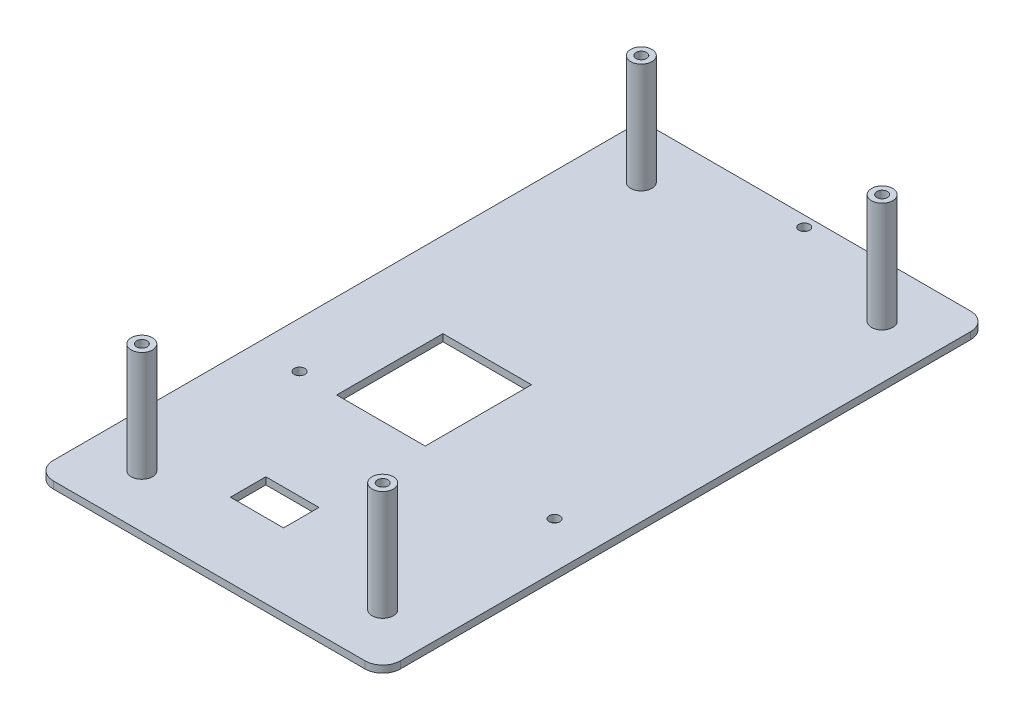
SolidWorks part; units mm, degrees
ref_plane "Alzado" through (0, 0, 0) normal (0, 0, 1) x (1, 0, 0)
ref_plane "Planta" through (0, 0, 0) normal (0, 1, 0) x (1, 0, 0)
ref_plane "Vista lateral" through (0, 0, 0) normal (1, 0, 0) x (0, 0, -1)
sketch "Croquis1" plane through (0, 0, 0) normal (0, 1, 0) x (1, 0, 0)
  line L0 (0, 5.5) -> (-25, 5.5)
  line L1 (-49, 85.5) -> (49, 85.5)
  line L2 (-49, 85.5) -> (-49, -85.5)
  line L3 (-49, -85.5) -> (49, -85.5)
  line L4 (49, 85.5) -> (49, -85.5)
  line L5 (-49, 85.5) -> (-42.196, 73.6277) construction
  line L6 (-49, -85.5) -> (49, 85.5) construction
  line L7 (0, -24.5) -> (-25, -24.5)
  line L8 (-25, 5.5) -> (-25, -24.5)
  line L9 (0, 0) -> (0, 5.5)
  line L10 (0, 5.5) -> (0, -24.5)
  line L11 (0, 0) -> (0, -8.409) construction
  line L12 (0, -64.5) -> (-15, -64.5)
  line L13 (0, -64.5) -> (0, -54.5)
  line L14 (0, -54.5) -> (-15, -54.5)
  line L15 (-15, -64.5) -> (-15, -54.5)
  point P0 (0, 0)
  dimension "D1" = 98
  dimension "D2" = 171
  dimension "D3" = 25
  dimension "D4" = 30
  dimension "D5" = 30
  dimension "D6" = 15
  dimension "D7" = 10
  dimension "D8" = 80
extrude "Saliente-Extruir1" add sketch "Croquis1" along normal blind 2 contours L4 L1 L2 L3 L9 L10 L7 L8 L0 L12 L15 L14 L13
fillet "Redondeo1" radius 5 4 edges at (49, 1, 85.5) (49, 1, -85.5) (-49, 1, -85.5) (-49, 1, 85.5)
sketch "Croquis2" plane through (0, 2, 0) normal (0, 1, 0) x (1, 0, 0)
  line L0 (0, -85.5) -> (0, 85.5) construction
  line L1 (-44, -85.5) -> (44, -85.5) construction
  line L2 (-44, 85.5) -> (44, 85.5) construction
  line L3 (-49, 80.5) -> (-49, -80.5) construction
  line L4 (49, 80.5) -> (49, -80.5) construction
  circle A0 centre (-36, -24) radius 1.5
  circle A1 centre (36, -24) radius 1.5
  circle A2 centre (0, 82.5) radius 1.5
  dimension "D1" = 3
  dimension "D2" = 3
  dimension "D3" = 61.5
  dimension "D5" = 13
  dimension "D7" = 3
  dimension "D4" = 61.5
  dimension "D6" = 13
  dimension "D8" = 106.5
extrude "Cortar-Extruir2" cut sketch "Croquis2" against normal blind 10 contours A1 | A0 | A2
sketch "Croquis5" plane through (0, 2, 0) normal (0, 1, 0) x (1, 0, 0)
  line L0 (-49, 80.5) -> (-49, -80.5) construction
  line L1 (-44, 85.5) -> (44, 85.5) construction
  line L2 (0, 0) -> (0, 85.5) construction
  line L3 (0, 0) -> (40.8647, 0) construction
  circle A0 centre (-34, 70.5) radius 3
  circle A1 centre (34, 70.5) radius 3
  circle A2 centre (34, -70.5) radius 3
  circle A3 centre (-34, -70.5) radius 3
  dimension "D2" = 15
  dimension "D3" = 6
  dimension "D4" = 6
  dimension "D1" = 15
extrude "Saliente-Extruir2" add sketch "Croquis5" along normal blind 31
sketch "Croquis6" plane through (0, 33, 0) normal (0, 1, 0) x (1, 0, 0)
  circle A0 centre (-34, 70.5) radius 1.5
  circle A1 centre (34, 70.5) radius 1.5
  circle A2 centre (34, -70.5) radius 1.5
  circle A3 centre (-34, -70.5) radius 1.5
  dimension "D1" = 3
extrude "Cortar-Extruir3" cut sketch "Croquis6" against normal blind 15
